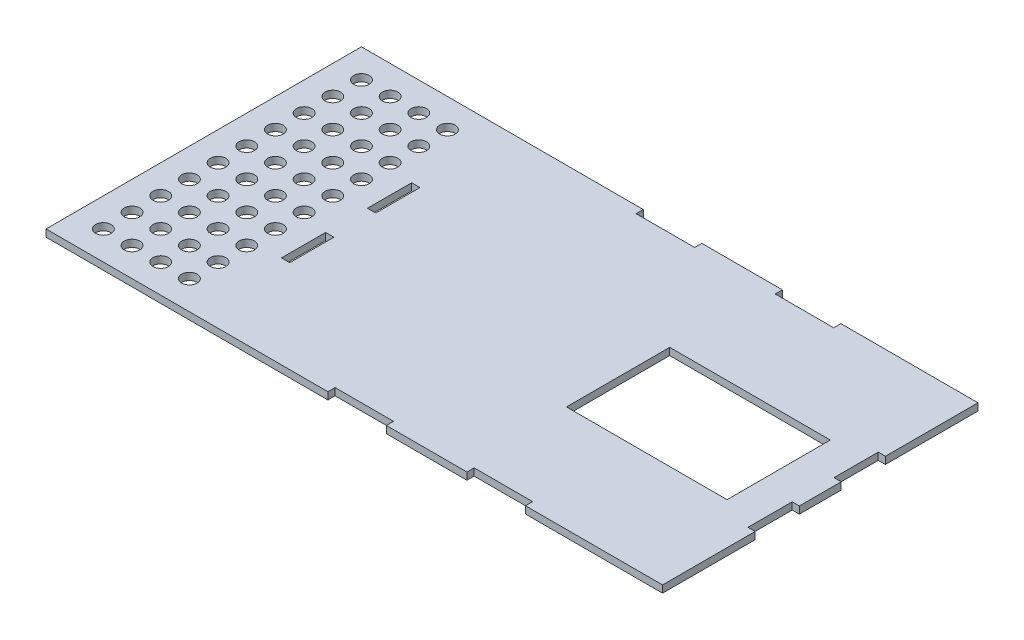
SolidWorks part; units mm, degrees
ref_plane "Front Plane" through (0, 0, 0) normal (0, 0, 1) x (1, 0, 0)
ref_plane "Top Plane" through (0, 0, 0) normal (0, 1, 0) x (1, 0, 0)
ref_plane "Right Plane" through (0, 0, 0) normal (1, 0, 0) x (0, 0, -1)
sketch "Sketch1" plane through (0, 0, 0) normal (0, 1, 0) x (1, 0, 0)
  line L1 (-101.6, -66.675) -> (101.6, -66.675)
  line L2 (-101.6, -66.675) -> (-101.6, 66.675)
  line L3 (-101.6, 66.675) -> (101.6, 66.675)
  line L4 (101.6, -66.675) -> (101.6, 66.675)
  line L5 (-101.6, -66.675) -> (101.6, 66.675) construction
  line L6 (-101.6, 66.675) -> (101.6, -66.675) construction
  point P0 (0, 0)
  dimension "D1" = 203.2
  dimension "D2" = 133.35
extrude "Boss-Extrude1" add sketch "Sketch1" along normal blind 3.175
sketch "Sketch3" plane through (0, 3.175, 0) normal (0, 1, 0) x (1, 0, 0)
  line L0 (101.6, 66.675) -> (-101.6, 66.675) construction
  line L1 (-79.121, 66.675) -> (-43.434, 66.675)
  line L2 (-79.121, 66.675) -> (-79.121, 69.85)
  line L3 (-79.121, 69.85) -> (-43.434, 69.85)
  line L4 (-43.434, 66.675) -> (-43.434, 69.85)
  line L5 (-101.6, 66.675) -> (-101.6, -66.675) construction
  line L6 (-17.526, 66.675) -> (18.161, 66.675)
  line L7 (18.161, 66.675) -> (18.161, 69.85)
  line L8 (-17.526, 69.85) -> (18.161, 69.85)
  line L9 (-17.526, 66.675) -> (-17.526, 69.85)
  line L10 (44.069, 66.675) -> (79.756, 66.675)
  line L11 (79.756, 66.675) -> (79.756, 69.85)
  line L12 (44.069, 69.85) -> (79.756, 69.85)
  line L13 (44.069, 66.675) -> (44.069, 69.85)
  line L14 (0, 0) -> (101.6, 0) construction
  line L15 (101.6, -66.675) -> (101.6, 66.675) construction
  line L16 (44.069, -66.675) -> (44.069, -69.85)
  line L17 (44.069, -69.85) -> (79.756, -69.85)
  line L18 (79.756, -66.675) -> (79.756, -69.85)
  line L19 (44.069, -66.675) -> (79.756, -66.675)
  line L20 (-17.526, -66.675) -> (-17.526, -69.85)
  line L21 (-17.526, -69.85) -> (18.161, -69.85)
  line L22 (18.161, -66.675) -> (18.161, -69.85)
  line L23 (-17.526, -66.675) -> (18.161, -66.675)
  line L24 (-43.434, -66.675) -> (-43.434, -69.85)
  line L25 (-79.121, -69.85) -> (-43.434, -69.85)
  line L26 (-79.121, -66.675) -> (-79.121, -69.85)
  line L27 (-79.121, -66.675) -> (-43.434, -66.675)
  point P6 (-61.2775, 66.675)
  dimension "D1" = 3.175
  dimension "D2" = 40.3225
  dimension "D3" = 22.479
  dimension "D4" = 35.687
  dimension "D5" = 3
extrude "Boss-Extrude2" add sketch "Sketch3" against normal blind 3.175
sketch "Sketch4" plane through (0, 3.175, 0) normal (0, 1, 0) x (1, 0, 0)
  line L0 (-101.6, 66.675) -> (-101.6, -66.675) construction
  line L1 (-101.6, 47.371) -> (-104.775, 47.371)
  line L2 (-101.6, 47.371) -> (-101.6, 28.829)
  line L3 (-101.6, 28.829) -> (-104.775, 28.829)
  line L4 (-104.775, 47.371) -> (-104.775, 28.829)
  line L5 (-104.775, 9.271) -> (-104.775, -9.271)
  line L6 (-79.121, 66.675) -> (-101.6, 66.675) construction
  line L7 (-101.6, -9.271) -> (-104.775, -9.271)
  line L8 (-101.6, 9.271) -> (-101.6, -9.271)
  line L9 (-101.6, 9.271) -> (-104.775, 9.271)
  line L10 (-104.775, -28.829) -> (-104.775, -47.371)
  line L11 (-101.6, -47.371) -> (-104.775, -47.371)
  line L12 (-101.6, -28.829) -> (-101.6, -47.371)
  line L13 (-101.6, -28.829) -> (-104.775, -28.829)
  line L14 (0, 0) -> (0, 30.8846) construction
  line L15 (101.6, -28.829) -> (104.775, -28.829)
  line L16 (101.6, -28.829) -> (101.6, -47.371)
  line L17 (101.6, -47.371) -> (104.775, -47.371)
  line L18 (104.775, -28.829) -> (104.775, -47.371)
  line L19 (101.6, 9.271) -> (104.775, 9.271)
  line L20 (101.6, 9.271) -> (101.6, -9.271)
  line L21 (101.6, -9.271) -> (104.775, -9.271)
  line L22 (104.775, 9.271) -> (104.775, -9.271)
  line L23 (104.775, 47.371) -> (104.775, 28.829)
  line L24 (101.6, 28.829) -> (104.775, 28.829)
  line L25 (101.6, 47.371) -> (101.6, 28.829)
  line L26 (101.6, 47.371) -> (104.775, 47.371)
  point P9 (-101.6, 38.1)
  point P10 (-103.1875, 47.371)
  dimension "D1" = 3.175
  dimension "D2" = 28.575
  dimension "D3" = 18.542
  dimension "D4" = 19.304
  dimension "D6" = 38.1
  dimension "D5" = 3
extrude "Boss-Extrude3" add sketch "Sketch4" against normal blind 3.175
sketch "Sketch5" plane through (0, 3.175, 0) normal (0, 1, 0) x (1, 0, 0)
  line L0 (-104.775, -28.829) -> (-104.775, -47.371) construction
  line L1 (-104.775, 69.85) -> (-168.275, 69.85)
  line L2 (-104.775, 69.85) -> (-104.775, -69.85)
  line L3 (-104.775, -69.85) -> (-168.275, -69.85)
  line L4 (-168.275, 69.85) -> (-168.275, -69.85)
  line L5 (-79.121, -69.85) -> (-43.434, -69.85) construction
  line L6 (-43.434, 69.85) -> (-79.121, 69.85) construction
  circle A0 centre (-117.475, 57.15) radius 3.429
  circle A1 centre (-130.175, 57.15) radius 3.429
  circle A2 centre (-142.875, 57.15) radius 3.429
  circle A3 centre (-155.575, 57.15) radius 3.429
  circle A4 centre (-130.175, 44.45) radius 3.429
  circle A5 centre (-142.875, 44.45) radius 3.429
  circle A6 centre (-155.575, 44.45) radius 3.429
  circle A7 centre (-130.175, 31.75) radius 3.429
  circle A8 centre (-142.875, 31.75) radius 3.429
  circle A9 centre (-155.575, 31.75) radius 3.429
  circle A10 centre (-130.175, 19.05) radius 3.429
  circle A11 centre (-142.875, 19.05) radius 3.429
  circle A12 centre (-155.575, 19.05) radius 3.429
  circle A13 centre (-130.175, 6.35) radius 3.429
  circle A14 centre (-142.875, 6.35) radius 3.429
  circle A15 centre (-155.575, 6.35) radius 3.429
  circle A16 centre (-130.175, -6.35) radius 3.429
  circle A17 centre (-142.875, -6.35) radius 3.429
  circle A18 centre (-155.575, -6.35) radius 3.429
  circle A19 centre (-130.175, -19.05) radius 3.429
  circle A20 centre (-142.875, -19.05) radius 3.429
  circle A21 centre (-155.575, -19.05) radius 3.429
  circle A22 centre (-130.175, -31.75) radius 3.429
  circle A23 centre (-142.875, -31.75) radius 3.429
  circle A24 centre (-155.575, -31.75) radius 3.429
  circle A25 centre (-130.175, -44.45) radius 3.429
  circle A26 centre (-142.875, -44.45) radius 3.429
  circle A27 centre (-155.575, -44.45) radius 3.429
  circle A28 centre (-130.175, -57.15) radius 3.429
  circle A29 centre (-142.875, -57.15) radius 3.429
  circle A30 centre (-155.575, -57.15) radius 3.429
  circle A31 centre (-117.475, 44.45) radius 3.429
  circle A32 centre (-117.475, 31.75) radius 3.429
  circle A33 centre (-117.475, 19.05) radius 3.429
  circle A34 centre (-117.475, 6.35) radius 3.429
  circle A35 centre (-117.475, -6.35) radius 3.429
  circle A36 centre (-117.475, -19.05) radius 3.429
  circle A37 centre (-117.475, -31.75) radius 3.429
  circle A38 centre (-117.475, -44.45) radius 3.429
  circle A39 centre (-117.475, -57.15) radius 3.429
  dimension "D1" = 6.858
  dimension "D6" = 63.5
  dimension "D2" = 12.7
  dimension "D3" = 12.7
  dimension "D4" = 4
  dimension "D5" = 10
extrude "Boss-Extrude4" add sketch "Sketch5" against normal blind 3.175
sketch "Sketch6" plane through (0, 3.175, 0) normal (0, 1, 0) x (1, 0, 0)
  line L6 (0, 0) -> (0, -69.8507) construction
  line L8 (0, 0) -> (104.775, 0) construction
  line L18 (-79.121, 66.675) -> (-79.121, 69.85)
  line L19 (-104.775, 69.85) -> (-79.121, 69.85)
  line L20 (-104.775, 58.6105) -> (-104.775, 69.85)
  line L21 (-101.6, 66.675) -> (-79.121, 66.675)
  line L22 (-104.775, 47.371) -> (-104.775, 69.85) construction
  line L23 (-101.6, 47.371) -> (-104.775, 47.371)
  line L24 (-101.6, 47.371) -> (-101.6, 66.675)
  line L26 (-104.775, 47.371) -> (-104.775, 58.6105)
  line L27 (-104.775, -47.371) -> (-104.775, -58.6105)
  line L28 (-101.6, -47.371) -> (-101.6, -66.675)
  line L29 (-101.6, -47.371) -> (-104.775, -47.371)
  line L30 (-101.6, -66.675) -> (-79.121, -66.675)
  line L31 (-104.775, -58.6105) -> (-104.775, -69.85)
  line L32 (-104.775, -69.85) -> (-79.121, -69.85)
  line L33 (-79.121, -66.675) -> (-79.121, -69.85)
  line L34 (79.121, -66.675) -> (79.121, -69.85)
  line L35 (104.775, -69.85) -> (79.121, -69.85)
  line L36 (104.775, -58.6105) -> (104.775, -69.85)
  line L37 (101.6, -66.675) -> (79.121, -66.675)
  line L38 (101.6, -47.371) -> (104.775, -47.371)
  line L39 (101.6, -47.371) -> (101.6, -66.675)
  line L40 (104.775, -47.371) -> (104.775, -58.6105)
  line L41 (104.775, 47.371) -> (104.775, 58.6105)
  line L42 (101.6, 47.371) -> (101.6, 66.675)
  line L43 (101.6, 47.371) -> (104.775, 47.371)
  line L44 (101.6, 66.675) -> (79.121, 66.675)
  line L45 (104.775, 58.6105) -> (104.775, 69.85)
  line L46 (104.775, 69.85) -> (79.121, 69.85)
  line L47 (79.121, 66.675) -> (79.121, 69.85)
extrude "Boss-Extrude5" add sketch "Sketch6" against normal blind 3.175
sketch "Sketch7" plane through (0, 3.175, 0) normal (0, 1, 0) x (1, 0, 0)
  line L0 (-101.6, -28.829) -> (-104.775, -28.829) construction
  line L1 (-101.346, 28.829) -> (-105.029, 28.829)
  line L2 (-101.346, 28.829) -> (-101.346, 9.271)
  line L3 (-101.346, 9.271) -> (-105.029, 9.271)
  line L4 (-105.029, 28.829) -> (-105.029, 9.271)
  line L5 (-105.029, -9.271) -> (-101.346, -9.271)
  line L6 (-105.029, -9.271) -> (-105.029, -28.829)
  line L7 (-105.029, -28.829) -> (-101.346, -28.829)
  line L8 (-101.346, -9.271) -> (-101.346, -28.829)
  line L9 (-104.775, -9.271) -> (-101.6, -9.271) construction
  line L10 (-101.6, 9.271) -> (-104.775, 9.271) construction
  line L11 (-104.775, 28.829) -> (-101.6, 28.829) construction
  point P16 (-103.1875, 28.829)
  dimension "D1" = 3.683
extrude "Cut-Extrude1" cut sketch "Sketch7" against normal through all
sketch "Sketch8" plane through (0, 0, 0) normal (0, 1, 0) x (1, 0, 0)
  line L0 (101.6, 9.271) -> (101.6, 28.829) construction
  line L1 (86.36, 22.86) -> (15.24, 22.86)
  line L2 (86.36, 22.86) -> (86.36, -22.86)
  line L3 (86.36, -22.86) -> (15.24, -22.86)
  line L4 (15.24, 22.86) -> (15.24, -22.86)
  line L5 (86.36, 22.86) -> (15.24, -22.86) construction
  line L6 (86.36, -22.86) -> (15.24, 22.86) construction
  point P0 (50.8, 0)
  point P5 (0, 0)
  dimension "D1" = 45.72
  dimension "D2" = 71.12
  dimension "D3" = 50.8
extrude "Cut-Extrude4" cut sketch "Sketch8" along normal through all
